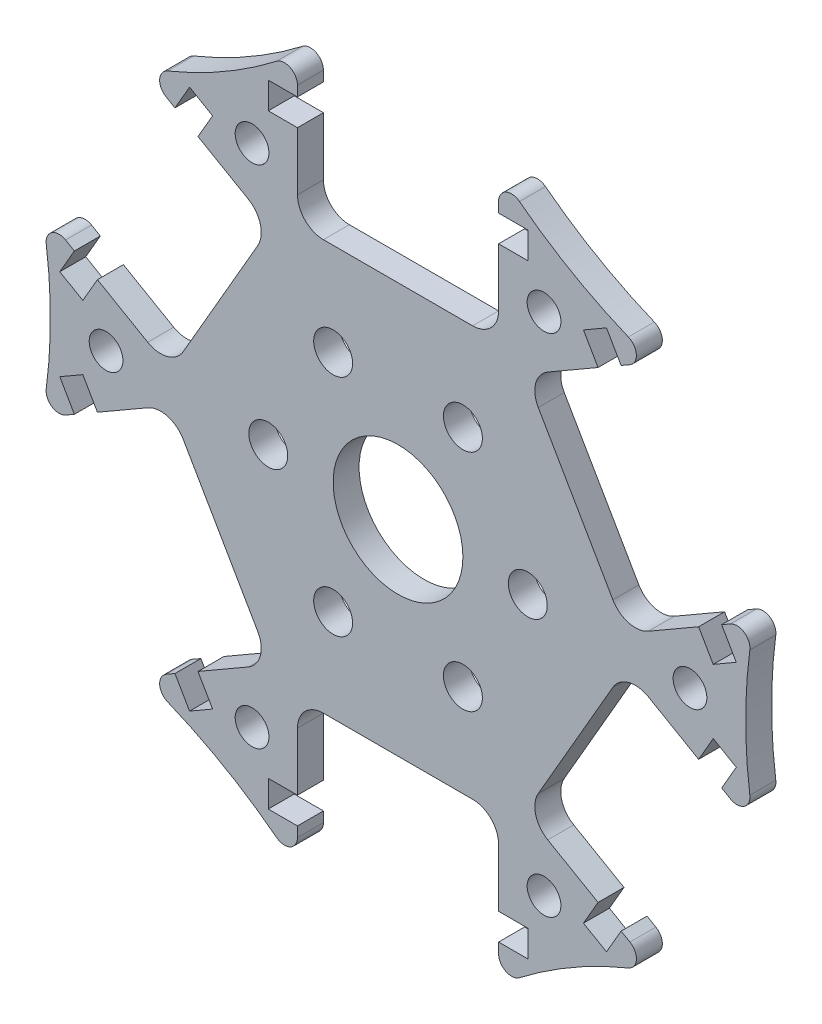
SolidWorks part; units mm, degrees
material "6061 合金"
ref_plane "Front" through (0, 0, 0) normal (0, 0, 1) x (1, 0, 0)
ref_plane "Top" through (0, 0, 0) normal (0, 1, 0) x (1, 0, 0)
ref_plane "Right" through (0, 0, 0) normal (1, 0, 0) x (0, 0, -1)
sketch "ｽｹｯﾁ1" plane through (0, 0, 0) normal (0, 0, 1) x (1, 0, 0)
  circle A0 centre (0, 0) radius 28.3
  dimension "D1" = 56.6
extrude "ﾎﾞｽ - 押し出し1" add sketch "ｽｹｯﾁ1" along normal blind 2
sketch "ｽｹｯﾁ2" plane through (0, 0, 2) normal (0, 0, 1) x (1, 0, 0)
  line L0 (0, 0) -> (0, 50000) construction
  line L1 (7.75, 24.325) -> (10, 24.325)
  line L2 (10, 24.325) -> (10, 22.275)
  line L3 (-7.75, 15.8) -> (-7.75, 22.275)
  line L4 (10, 22.275) -> (7.75, 22.275)
  line L5 (7.75, 27.2181) -> (7.75, 24.325)
  line L6 (7.75, 22.275) -> (7.75, 15.8)
  line L7 (7.75, 15.8) -> (-7.75, 15.8)
  line L8 (-7.75, 22.275) -> (-10, 22.275)
  line L9 (-10, 22.275) -> (-10, 24.325)
  line L10 (-10, 24.325) -> (-7.75, 24.325)
  line L11 (-7.75, 24.325) -> (-7.75, 27.2181)
  line L12 (0, 28.3) -> (16.8233, 28.3) construction
  line L13 (10, 23.3) -> (-10, 23.3) construction
  line L14 (0, 0) -> (28.3, 0) construction
  line L15 (24.9411, 5.4508) -> (26.0661, 3.5022)
  line L16 (26.0661, 3.5022) -> (24.2907, 2.4772)
  line L17 (9.8082, 14.6117) -> (15.4157, 17.8492)
  line L18 (24.2907, 2.4772) -> (23.1657, 4.4258)
  line L19 (27.4466, 6.8974) -> (24.9411, 5.4508)
  line L20 (23.1657, 4.4258) -> (17.5582, 1.1883)
  line L21 (17.5582, 1.1883) -> (9.8082, 14.6117)
  line L22 (15.4157, 17.8492) -> (14.2907, 19.7978)
  line L23 (14.2907, 19.7978) -> (16.0661, 20.8228)
  line L24 (16.0661, 20.8228) -> (17.1911, 18.8742)
  line L25 (17.1911, 18.8742) -> (19.6966, 20.3208)
  line L26 (25.1784, 2.9897) -> (15.1784, 20.3103) construction
  line L27 (17.1911, -18.8742) -> (16.0661, -20.8228)
  line L28 (16.0661, -20.8228) -> (14.2907, -19.7978)
  line L29 (17.5582, -1.1883) -> (23.1657, -4.4258)
  line L30 (14.2907, -19.7978) -> (15.4157, -17.8492)
  line L31 (19.6966, -20.3208) -> (17.1911, -18.8742)
  line L32 (15.4157, -17.8492) -> (9.8082, -14.6117)
  line L33 (9.8082, -14.6117) -> (17.5582, -1.1883)
  line L34 (23.1657, -4.4258) -> (24.2907, -2.4772)
  line L35 (24.2907, -2.4772) -> (26.0661, -3.5022)
  line L36 (26.0661, -3.5022) -> (24.9411, -5.4508)
  line L37 (24.9411, -5.4508) -> (27.4466, -6.8974)
  line L38 (15.1784, -20.3103) -> (25.1784, -2.9897) construction
  line L39 (-7.75, -24.325) -> (-10, -24.325)
  line L40 (-10, -24.325) -> (-10, -22.275)
  line L41 (7.75, -15.8) -> (7.75, -22.275)
  line L42 (-10, -22.275) -> (-7.75, -22.275)
  line L43 (-7.75, -27.2181) -> (-7.75, -24.325)
  line L44 (-7.75, -22.275) -> (-7.75, -15.8)
  line L45 (-7.75, -15.8) -> (7.75, -15.8)
  line L46 (7.75, -22.275) -> (10, -22.275)
  line L47 (10, -22.275) -> (10, -24.325)
  line L48 (10, -24.325) -> (7.75, -24.325)
  line L49 (7.75, -24.325) -> (7.75, -27.2181)
  line L50 (-10, -23.3) -> (10, -23.3) construction
  line L51 (-24.9411, -5.4508) -> (-26.0661, -3.5022)
  line L52 (-26.0661, -3.5022) -> (-24.2907, -2.4772)
  line L53 (-9.8082, -14.6117) -> (-15.4157, -17.8492)
  line L54 (-24.2907, -2.4772) -> (-23.1657, -4.4258)
  line L55 (-27.4466, -6.8974) -> (-24.9411, -5.4508)
  line L56 (-23.1657, -4.4258) -> (-17.5582, -1.1883)
  line L57 (-17.5582, -1.1883) -> (-9.8082, -14.6117)
  line L58 (-15.4157, -17.8492) -> (-14.2907, -19.7978)
  line L59 (-14.2907, -19.7978) -> (-16.0661, -20.8228)
  line L60 (-16.0661, -20.8228) -> (-17.1911, -18.8742)
  line L61 (-17.1911, -18.8742) -> (-19.6966, -20.3208)
  line L62 (-25.1784, -2.9897) -> (-15.1784, -20.3103) construction
  line L63 (-17.1911, 18.8742) -> (-16.0661, 20.8228)
  line L64 (-16.0661, 20.8228) -> (-14.2907, 19.7978)
  line L65 (-17.5582, 1.1883) -> (-23.1657, 4.4258)
  line L66 (-14.2907, 19.7978) -> (-15.4157, 17.8492)
  line L67 (-19.6966, 20.3208) -> (-17.1911, 18.8742)
  line L68 (-15.4157, 17.8492) -> (-9.8082, 14.6117)
  line L69 (-9.8082, 14.6117) -> (-17.5582, 1.1883)
  line L70 (-23.1657, 4.4258) -> (-24.2907, 2.4772)
  line L71 (-24.2907, 2.4772) -> (-26.0661, 3.5022)
  line L72 (-26.0661, 3.5022) -> (-24.9411, 5.4508)
  line L73 (-24.9411, 5.4508) -> (-27.4466, 6.8974)
  line L74 (-15.1784, 20.3103) -> (-25.1784, 2.9897) construction
  line L75 (0, 0) -> (5, 8.6603) construction
  line L76 (0, 0) -> (11.25, 19.4856) construction
  arc A0 (7.75, 27.2181) -> (-7.75, 27.2181) centre (0, 0) ccw
  circle A1 centre (0, 0) radius 28.3 construction
  circle A2 centre (0, 0) radius 5
  circle A3 centre (0, 0) radius 10 construction
  arc A4 (27.4466, 6.8974) -> (19.6966, 20.3208) centre (0, 0) ccw
  arc A5 (19.6966, -20.3208) -> (27.4466, -6.8974) centre (0, 0) ccw
  arc A6 (-7.75, -27.2181) -> (7.75, -27.2181) centre (0, 0) ccw
  arc A7 (-27.4466, -6.8974) -> (-19.6966, -20.3208) centre (0, 0) ccw
  arc A8 (-19.6966, 20.3208) -> (-27.4466, 6.8974) centre (0, 0) ccw
  circle A9 centre (5, 8.6603) radius 1.5
  circle A10 centre (10, 0) radius 1.5
  circle A11 centre (5, -8.6603) radius 1.5
  circle A12 centre (-5, -8.6603) radius 1.5
  circle A13 centre (-10, 0) radius 1.5
  circle A14 centre (-5, 8.6603) radius 1.5
  circle A15 centre (0, 0) radius 22.5 construction
  circle A16 centre (11.25, 19.4856) radius 1.3
  circle A17 centre (22.5, 0) radius 1.3
  circle A18 centre (11.25, -19.4856) radius 1.3
  circle A19 centre (-11.25, -19.4856) radius 1.3
  circle A20 centre (-22.5, 0) radius 1.3
  circle A21 centre (-11.25, 19.4856) radius 1.3
  point P99 (0, 0)
  point P111 (0, 0)
  dimension "D1" = 15.5
  dimension "D6" = 10
  dimension "D7" = 20
  dimension "D9" = 60
  dimension "D10" = 3
  dimension "D12" = 45
  dimension "D13" = 2.6
  dimension "D2" = 20
  dimension "D3" = 2.05
  dimension "D4" = 12.5
  dimension "D5" = 5
  dimension "D8" = 6
  dimension "D11" = 6
extrude "ｶｯﾄ - 押し出し1" cut sketch "ｽｹｯﾁ2" against normal through all
sketch "ｽｹｯﾁ3" plane through (0, 0, 2) normal (0, 0, 1) x (1, 0, 0)
  line L0 (0, 0) -> (14.15, 24.5085) construction
  arc A0 (19.6966, 20.3208) -> (7.75, 27.2181) centre (0, 0) ccw construction
  arc A1 (7.75, 27.2181) -> (19.6966, 20.3208) centre (31.65, 54.8194) ccw
  arc A2 (19.6966, 20.3208) -> (7.75, 27.2181) centre (0, 0) ccw
  arc A3 (27.4466, 6.8974) -> (27.4466, -6.8974) centre (63.3, 0) ccw
  arc A4 (27.4466, -6.8974) -> (27.4466, 6.8974) centre (0, 0) ccw
  arc A5 (19.6966, -20.3208) -> (7.75, -27.2181) centre (31.65, -54.8194) ccw
  arc A6 (7.75, -27.2181) -> (19.6966, -20.3208) centre (0, 0) ccw
  arc A7 (-7.75, -27.2181) -> (-19.6966, -20.3208) centre (-31.65, -54.8194) ccw
  arc A8 (-19.6966, -20.3208) -> (-7.75, -27.2181) centre (0, 0) ccw
  arc A9 (-27.4466, -6.8974) -> (-27.4466, 6.8974) centre (-63.3, 0) ccw
  arc A10 (-27.4466, 6.8974) -> (-27.4466, -6.8974) centre (0, 0) ccw
  arc A11 (-19.6966, 20.3208) -> (-7.75, 27.2181) centre (-31.65, 54.8194) ccw
  arc A12 (-7.75, 27.2181) -> (-19.6966, 20.3208) centre (0, 0) ccw
  point P27 (0, 0)
  dimension "D1" = 35
  dimension "D2" = 6
extrude "ｶｯﾄ - 押し出し3" cut sketch "ｽｹｯﾁ3" against normal through all
fillet "ﾌｨﾚｯﾄ2" radius 2 12 edges at (-9.8082, 14.6117, 1) (-17.5582, -1.1883, 1) (-17.5582, 1.1883, 1) (-7.75, -15.8, 1) (-9.8082, -14.6117, 1) (9.8082, -14.6117, 1) (7.75, -15.8, 1) (17.5582, -1.1883, 1) (17.5582, 1.1883, 1) (9.8082, 14.6117, 1) (7.75, 15.8, 1) (-7.75, 15.8, 1)
fillet "ﾌｨﾚｯﾄ1" radius 1 12 edges at (19.6966, 20.3208, 1) (7.75, 27.2181, 1) (-19.6966, 20.3208, 1) (-7.75, 27.2181, 1) (-27.4466, 6.8974, 1) (-27.4466, -6.8974, 1) (-19.6966, -20.3208, 1) (-7.75, -27.2181, 1) (7.75, -27.2181, 1) (19.6966, -20.3208, 1) (27.4466, -6.8974, 1) (27.4466, 6.8974, 1)
